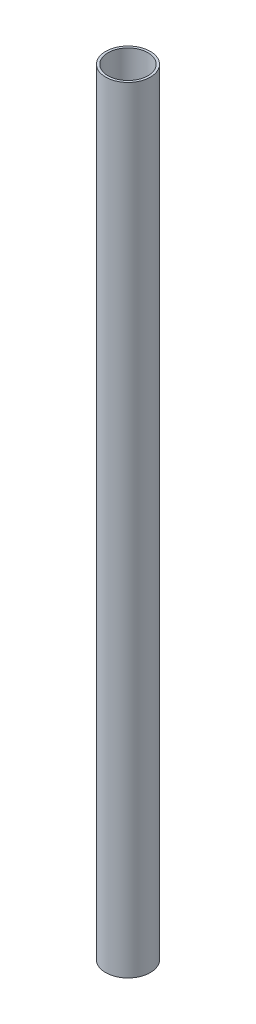
SolidWorks part; units mm, degrees
ref_plane "Front Plane" through (0, 0, 0) normal (0, 0, 1) x (1, 0, 0)
ref_plane "Top Plane" through (0, 0, 0) normal (0, 1, 0) x (1, 0, 0)
ref_plane "Right Plane" through (0, 0, 0) normal (1, 0, 0) x (0, 0, -1)
sketch "Sketch1" plane through (0, 0, 0) normal (0, 1, 0) x (1, 0, 0)
  circle A0 centre (0, 0) radius 9.5
  circle A1 centre (0, 0) radius 8.5
  dimension "D1" = 19
  dimension "D2" = 17
extrude "Boss-Extrude1" add sketch "Sketch1" along normal blind 330
